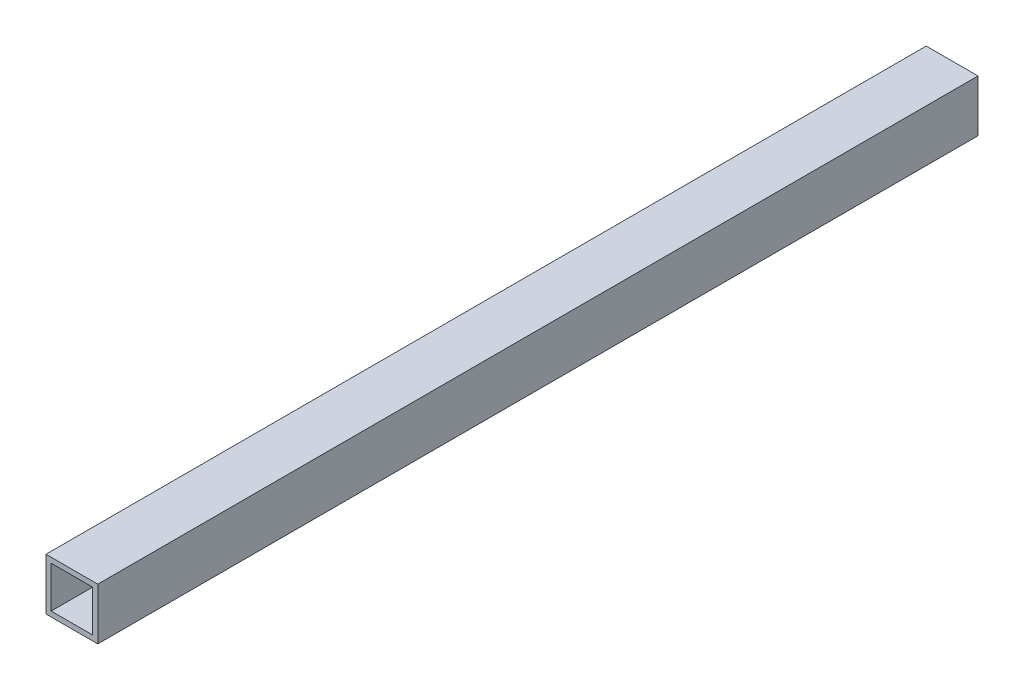
SolidWorks part; units mm, degrees
ref_plane "前视基准面" through (0, 0, 0) normal (0, 0, 1) x (1, 0, 0)
ref_plane "上视基准面" through (0, 0, 0) normal (0, 1, 0) x (1, 0, 0)
ref_plane "右视基准面" through (0, 0, 0) normal (1, 0, 0) x (0, 0, -1)
other "Configuration Table"
sketch "草图1" plane through (0, 0, 0) normal (0, 0, 1) x (1, 0, 0)
  line L1 (-10, -10) -> (10, -10)
  line L2 (-10, -10) -> (-10, 10)
  line L3 (-10, 10) -> (10, 10)
  line L4 (10, -10) -> (10, 10)
  line L5 (-10, -10) -> (10, 10) construction
  line L6 (-10, 10) -> (10, -10) construction
  line L7 (-8, -8) -> (8, -8)
  line L8 (-8, -8) -> (-8, 8)
  line L9 (-8, 8) -> (8, 8)
  line L10 (8, -8) -> (8, 8)
  line L11 (-8, -8) -> (8, 8) construction
  line L12 (-8, 8) -> (8, -8) construction
  point P0 (0, 0)
  point P6 (0, 0)
  dimension "D1" = 20
  dimension "D2" = 2
extrude "凸台-拉伸1" add sketch "草图1" along normal blind 340 contours L1 L4 L3 L2 L10 L7 L8 L9
